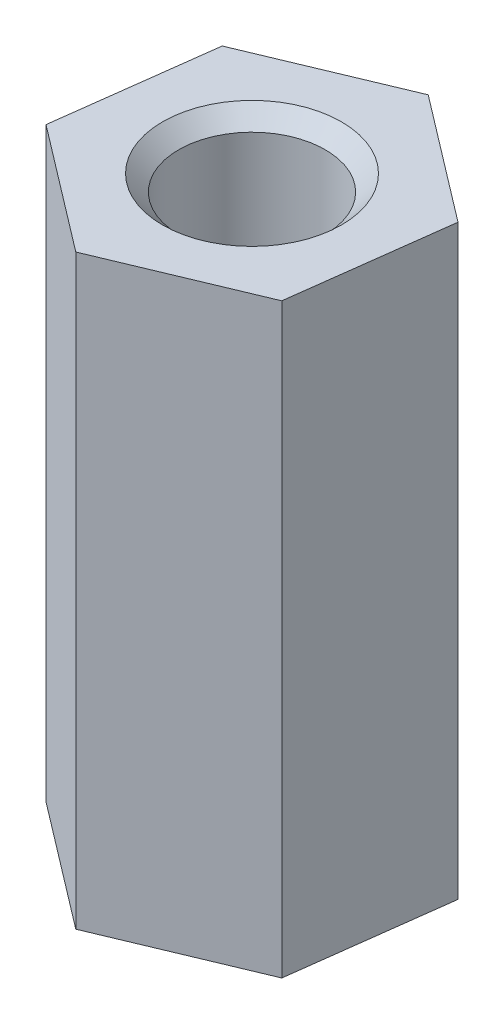
SolidWorks part; units mm, degrees
ref_plane "前视基准面" through (0, 0, 0) normal (0, 0, 1) x (1, 0, 0)
ref_plane "上视基准面" through (0, 0, 0) normal (0, 1, 0) x (1, 0, 0)
ref_plane "右视基准面" through (0, 0, 0) normal (1, 0, 0) x (0, 0, -1)
sketch "草图1" plane through (0, 0, 0) normal (0, 1, 0) x (1, 0, 0)
  line L1 (2.1352, -1.6273) -> (2.4769, 1.0355)
  line L2 (2.4769, 1.0355) -> (0.3417, 2.6628)
  line L3 (0.3417, 2.6628) -> (-2.1352, 1.6273)
  line L4 (-2.1352, 1.6273) -> (-2.4769, -1.0355)
  line L5 (-2.4769, -1.0355) -> (-0.3417, -2.6628)
  line L6 (-0.3417, -2.6628) -> (2.1352, -1.6273)
  circle A0 centre (0, 0) radius 2.325 construction
  dimension "D1" = 4.65
extrude "凸台-拉伸1" add sketch "草图1" along normal blind 10 contours L5 L6 L1 L2 L3 L4
sketch "草图2" plane through (0, 10, 0) normal (0, 1, 0) x (1, 0, 0)
  circle A0 centre (0, 0) radius 1.5
  dimension "D1" = 3
hole_wizard "M3 螺纹孔1" positions "草图6" profile "草图7" tap size "M3" standard "GB" end condition through all
sketch "草图6" plane through (0, 10, 0) normal (0, 1, 0) x (1, 0, 0)
  point P0 (0, 0)
sketch "草图7" plane through (0, 10, 0) normal (1, 0, 0) x (0, 0, 1)
  line L0 (0, 0) -> (0, 10)
  line L1 (0, 10) -> (1.25, 10)
  line L2 (1.25, 10) -> (1.25, 0.275)
  line L3 (1.25, 0.275) -> (1.525, 0)
  line L5 (1.525, 0) -> (0, 0)
  line L6 (-1.25, 0.275) -> (-1.525, 0) construction
  line L11 (0, -6.35) -> (0, 107.95) construction
  dimension "通孔螺纹孔钻头直径" = 2.5
  dimension "通孔螺纹孔钻头深度" = 10
  dimension "近端锥形沉头孔直径" = 3.05
  dimension "近端锥形沉头孔角度" = 90
cosmetic thread "孔螺蚊线1"
